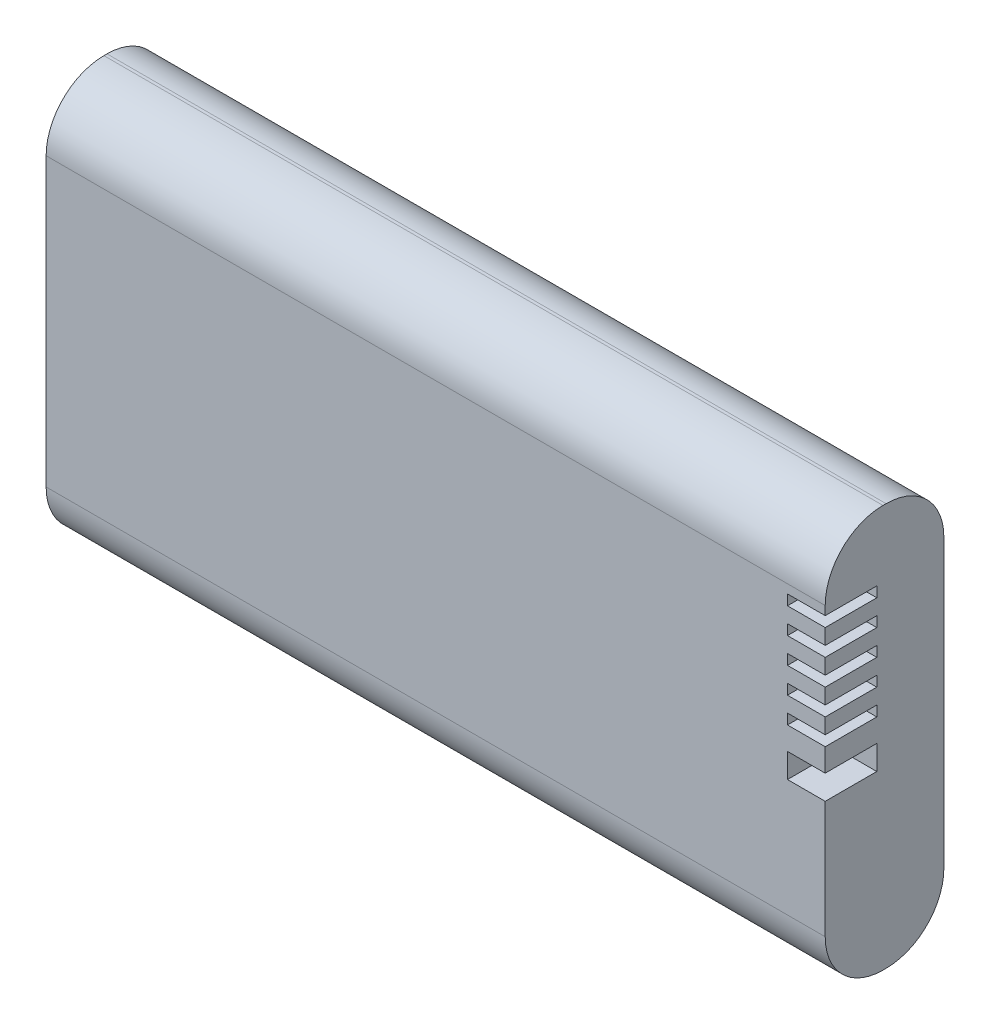
SolidWorks part; units mm, degrees
ref_plane "Plan de face" through (0, 0, 0) normal (0, 0, 1) x (1, 0, 0)
ref_plane "Plan de dessus" through (0, 0, 0) normal (0, 1, 0) x (1, 0, 0)
ref_plane "Plan de droite" through (0, 0, 0) normal (1, 0, 0) x (0, 0, -1)
sketch "Esquisse2" plane through (0, 0, 0) normal (0, 0, 1) x (1, 0, 0)
  line L0 (-99.5909, 29.5307) -> (51.4091, 29.5307)
  line L1 (-99.5909, 29.5307) -> (-99.5909, -48.4693)
  line L2 (-99.5909, -48.4693) -> (51.4091, -48.4693)
  line L3 (51.4091, 29.5307) -> (51.4091, -48.4693)
  dimension "D1" = 151
  dimension "D2" = 78
extrude "Boss.-Extru.1" add sketch "Esquisse2" along normal blind 23
sketch "Esquisse3" plane through (51.4091, 0, 0) normal (1, 0, 0) x (0, 0, -1)
  line L0 (-23, -48.4693) -> (-23, 29.5307) construction
  line L1 (-13, 6.6307) -> (-23, 6.6307)
  line L2 (-13, 6.6307) -> (-13, 4.6307)
  line L3 (-13, 4.6307) -> (-23, 4.6307)
  line L4 (-23, 6.6307) -> (-23, 4.6307)
  line L5 (-13, 11.6307) -> (-13, 9.6307)
  line L6 (-13, -9.8093) -> (-23, -9.8093)
  line L7 (-13, -9.8093) -> (-13, -14.5293)
  line L8 (-13, -14.5293) -> (-23, -14.5293)
  line L9 (-23, -9.8093) -> (-23, -14.5293)
  line L10 (-13, 11.6307) -> (-23, 11.6307)
  line L11 (-23, 11.6307) -> (-23, 9.6307)
  line L12 (-13, 9.6307) -> (-23, 9.6307)
  line L13 (-13, 16.6307) -> (-13, 14.6307)
  line L14 (-13, 16.6307) -> (-23, 16.6307)
  line L15 (-23, 16.6307) -> (-23, 14.6307)
  line L16 (-13, 14.6307) -> (-23, 14.6307)
  line L17 (-13, 1.6307) -> (-13, -0.3693)
  line L18 (-13, 1.6307) -> (-23, 1.6307)
  line L19 (-23, 1.6307) -> (-23, -0.3693)
  line L20 (-13, -0.3693) -> (-23, -0.3693)
  line L21 (-13, -3.3693) -> (-13, -5.3693)
  line L22 (-13, -3.3693) -> (-23, -3.3693)
  line L23 (-23, -3.3693) -> (-23, -5.3693)
  line L24 (-13, -5.3693) -> (-23, -5.3693)
  point P10 (-23, -9.4693)
  point P11 (-23, -12.1693)
  point P12 (-23, 5.6307)
  dimension "D1" = 10
  dimension "D2" = 4.72
  dimension "D3" = 2.7
  dimension "D4" = 15.1
  dimension "D5" = 2
  dimension "D6" = 3
  dimension "D7" = 3
extrude "Enlèv. mat.-Extru.1" cut sketch "Esquisse3" against normal blind 7.31
fillet "Congé1" radius 11.2 4 edges at (-24.0909, -48.4693, 23) (-24.0909, -48.4693, 0) (-24.0909, 29.5307, 23) (-24.0909, 29.5307, 0)
